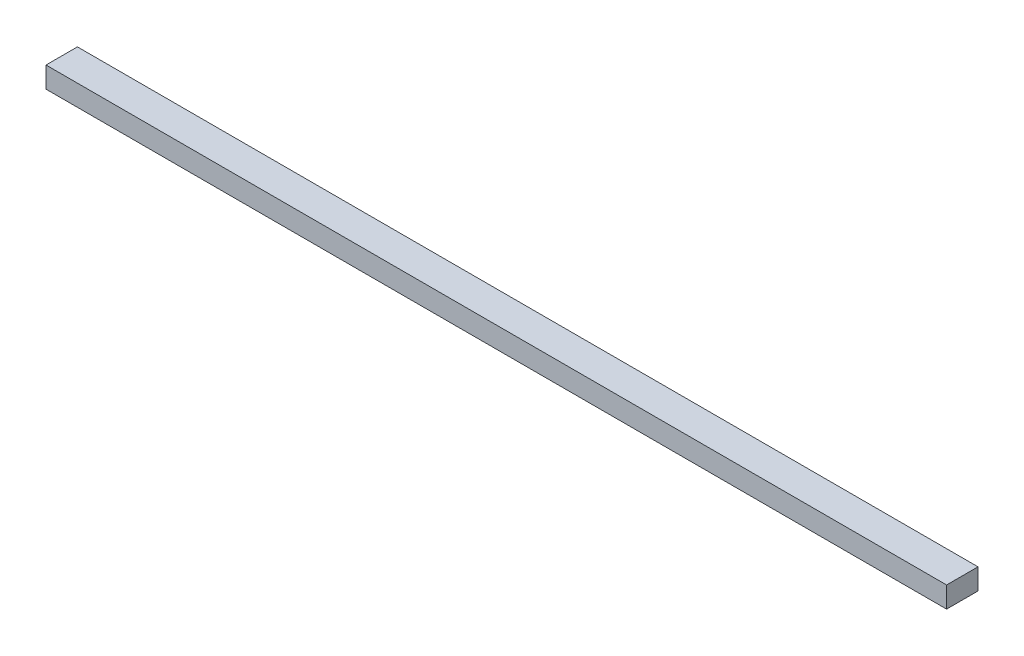
SolidWorks part; units mm, degrees
ref_plane "Front Plane" through (0, 0, 0) normal (0, 0, 1) x (1, 0, 0)
ref_plane "Top Plane" through (0, 0, 0) normal (0, 1, 0) x (1, 0, 0)
ref_plane "Right Plane" through (0, 0, 0) normal (1, 0, 0) x (0, 0, -1)
sketch "Sketch2" plane through (0, 0, 0) normal (0, 0, 1) x (1, 0, 0)
  line L1 (-43, 1) -> (43, 1)
  line L2 (-43, 1) -> (-43, -1)
  line L3 (-43, -1) -> (43, -1)
  line L4 (43, 1) -> (43, -1)
  line L5 (-43, 1) -> (43, -1) construction
  line L6 (-43, -1) -> (43, 1) construction
  point P0 (0, 0)
  dimension "D1" = 86
  dimension "D2" = 2
extrude "Boss-Extrude1" add sketch "Sketch2" along normal blind 3
